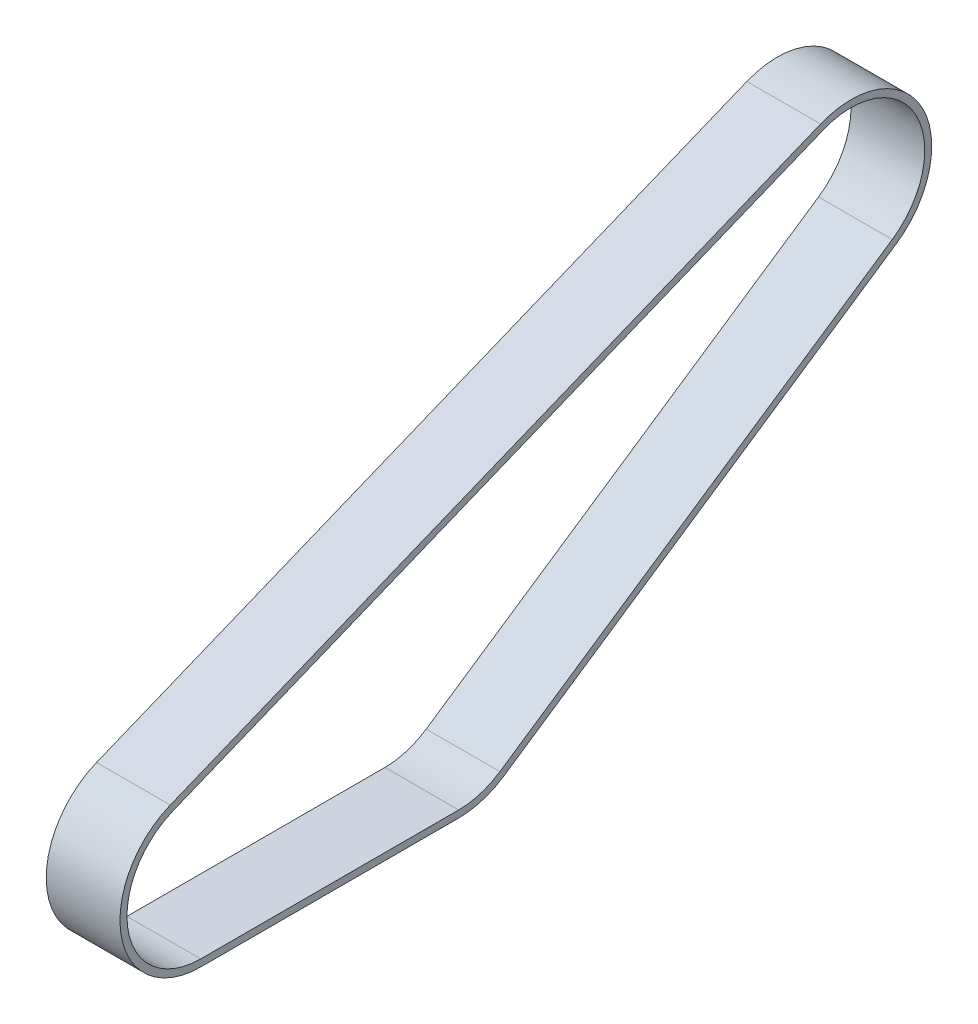
SolidWorks part; units mm, degrees
ref_plane "정면" through (0, 0, 0) normal (0, 0, 1) x (1, 0, 0)
ref_plane "윗면" through (0, 0, 0) normal (0, 1, 0) x (1, 0, 0)
ref_plane "우측면" through (0, 0, 0) normal (1, 0, 0) x (0, 0, -1)
sketch "스케치1" plane through (0, 0, 0) normal (1, 0, 0) x (0, 0, -1)
  line L0 (-47.4048, 0) -> (393.7152, 0) construction
  line L1 (-66.2502, 46.3125) -> (374.8698, 225.8125)
  line L2 (155.5548, -41.4519) -> (421.6748, 138.0481)
  line L3 (-47.4048, -50) -> (127.5952, -50)
  line L4 (-68.0413, 50.7141) -> (373.0787, 230.2141)
  line L5 (158.2121, -45.3915) -> (424.3321, 134.1085)
  line L6 (-47.4048, -54.752) -> (127.5952, -54.752)
  arc A0 (-66.2502, 46.3125) -> (-47.4048, -50) centre (-47.4048, 0) ccw
  arc A1 (127.5952, -50) -> (155.5548, -41.4519) centre (127.5952, 0) ccw
  arc A2 (421.6748, 138.0481) -> (374.8698, 225.8125) centre (393.7152, 179.5) ccw
  arc A3 (424.3321, 134.1085) -> (373.0787, 230.2141) centre (393.7152, 179.5) ccw
  arc A4 (127.5952, -54.752) -> (158.2121, -45.3915) centre (127.5952, 0) ccw
  arc A5 (-68.0413, 50.7141) -> (-47.4048, -54.752) centre (-47.4048, 0) ccw
  dimension "D1" = 100
  dimension "D2" = 100
  dimension "D3" = 100
  dimension "D4" = 175
  dimension "D5" = 441.12
  dimension "D6" = 179.5
  dimension "D7" = 4.752
extrude "보스-돌출1" add sketch "스케치1" along normal blind 50
